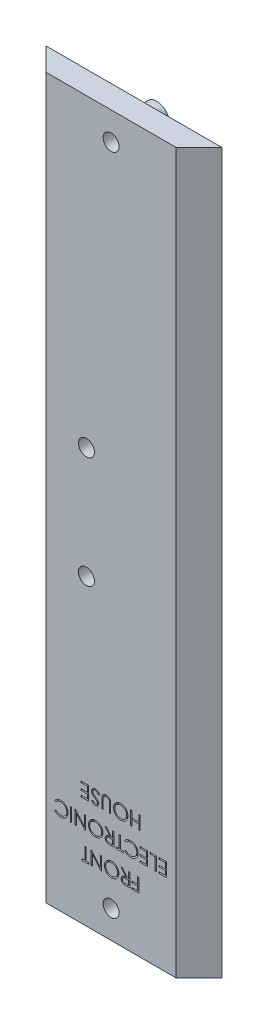
SolidWorks part; units mm, degrees
ref_plane "Front Plane" through (0, 0, 0) normal (1, 0, 0) x (0, 1, 0)
ref_plane "Top Plane" through (0, 0, 0) normal (0, 0, 1) x (0, 1, 0)
ref_plane "Right Plane" through (0, 0, 0) normal (0, 1, 0) x (-1, 0, 0)
sketch "Sketch3" plane through (0, 0, 0) normal (0, 0, 1) x (0, 1, 0)
  line L1 (0, 0) -> (157, 0)
  line L2 (0, 0) -> (0, 39.86)
  line L3 (0, 39.86) -> (157, 39.86)
  line L4 (157, 0) -> (157, 39.86)
extrude "Boss-Extrude1" add sketch "Sketch3" along normal blind 5
sketch "Sketch4" plane through (0, 0, 0) normal (0, -1, 0) x (1, 0, 0)
  line L0 (-39.86, 5) -> (-34.8616, 5)
  line L5 (-39.86, 5) -> (0, 5) construction
  line L6 (-34.8616, 5) -> (-39.86, 0)
  line L7 (-39.86, 0) -> (-39.86, 5)
  line L8 (0, 0) -> (0, 5)
  line L9 (0, 5) -> (-5, 5)
  line L10 (-5, 5) -> (0, 0)
extrude "Cut-Extrude2" cut sketch "Sketch4" against normal blind 157
sketch "Sketch6" plane through (0, 0, 5) normal (0, 0, 1) x (1, 0, 0)
  line L0 (-34.8616, 157) -> (-5, 0) construction
  line L1 (-5, 157) -> (-34.8616, 0) construction
  line L3 (-34.8616, 78.5) -> (-25.3316, 78.5) construction
  line L4 (-34.8616, 157) -> (-34.8616, 0) construction
  line L5 (-25.3316, 90.7) -> (-25.3316, 66.3) construction
  circle A0 centre (-19.9308, 6.08) radius 1.75
  circle A5 centre (-19.9308, 151.28) radius 1.75
  circle A6 centre (-25.3316, 90.7) radius 1.75
  circle A7 centre (-25.3316, 66.3) radius 1.75
  point P19 (-19.9308, 78.5)
  point P26 (-25.3316, 78.5)
extrude "Cut-Extrude3" cut sketch "Sketch6" against normal blind 5
sketch "Sketch7" plane through (0, 0, 0) normal (0, 0, -1) x (1, 0, 0)
  line L0 (-33.801, -65.3122) -> (-16.8606, -67.2423) construction
  line L1 (-16.8606, -67.2423) -> (-16.9738, -68.2359) construction
  line L2 (-33.801, -65.3122) -> (-36.9673, -93.1024) construction
  line L3 (-36.9673, -93.1024) -> (-33.7807, -93.523) construction
  line L4 (-33.7807, -93.523) -> (-33.801, -65.3122) construction
  line L5 (-16.9738, -68.2359) -> (-16.9738, -67.5359) construction
  circle A0 centre (-26.33, -20) radius 2.75
  circle A1 centre (-13.53, -20) radius 2.75
  circle A2 centre (-13.53, -40.35) radius 2.75
  circle A3 centre (-26.33, -40.35) radius 2.75
  circle A8 centre (-19.9308, -6.08) radius 2.75
  circle A10 centre (-19.9308, -151.28) radius 2.75
  circle A13 centre (-33.7807, -93.523) radius 2.75
  circle A14 centre (-33.801, -65.3122) radius 2.75
  circle A15 centre (-16.9738, -68.2359) radius 2.75 construction
  circle A16 centre (-16.9738, -67.5359) radius 2.75
  point P18 (-19.9308, -66.3)
sketch "Sketch8" plane through (0, 0, 0) normal (0, 0, -1) x (1, 0, 0)
  line L0 (-25.3316, -66.3) -> (-25.3316, -65.31) construction
  line L1 (-25.3316, -65.31) -> (-33.8016, -65.31) construction
  line L2 (-25.3316, -66.3) -> (-16.9716, -66.3) construction
  line L3 (-16.9716, -66.3) -> (-16.9716, -67.54) construction
  line L4 (-25.3316, -90.7) -> (-33.7816, -90.7) construction
  line L5 (-33.7816, -90.7) -> (-33.7816, -93.52) construction
  circle A0 centre (-26.33, -20) radius 1.7124
  circle A3 centre (-26.33, -40.35) radius 1.7124
  circle A7 centre (-13.53, -40.35) radius 1.7124
  circle A8 centre (-13.53, -20) radius 1.7124
  circle A10 centre (-19.9308, -6.08) radius 1.7124
  circle A12 centre (-19.9308, -151.28) radius 1.75
  circle A13 centre (-33.8016, -65.31) radius 1.75
  circle A14 centre (-16.9716, -67.54) radius 1.75
  circle A15 centre (-33.7816, -93.52) radius 1.75
extrude "Boss-Extrude3" add sketch "Sketch7" along normal blind 5
extrude "Cut-Extrude5" cut sketch "Sketch8" along normal blind 5
sketch "Sketch12" plane through (0, 157, 0) normal (0, 1, 0) x (-1, 0, 0)
  line L0 (0, 0) -> (0.3946, -0.307)
  line L1 (0.3946, -0.307) -> (5.7017, 5)
  line L2 (5, 5) -> (34.8616, 5) construction
  line L3 (5.7017, 5) -> (5, 5)
  line L4 (5, 5) -> (0, 0)
  line L5 (39.86, 0) -> (39.5064, -0.3536)
  line L6 (39.5064, -0.3536) -> (34.1529, 5)
  line L7 (34.1529, 5) -> (34.8616, 5)
  line L8 (34.8616, 5) -> (39.86, 0)
extrude "Cut-Extrude8" cut sketch "Sketch12" against normal blind 157
sketch "Sketch13" plane through (0, 157, 0) normal (0, 1, 0) x (-1, 0, 0)
  line L0 (0.7017, 0) -> (5.7017, 5)
  line L1 (5.7017, 5) -> (34.1529, 5)
  line L2 (34.1529, 5) -> (39.1529, 0)
  line L3 (0.7017, 0) -> (39.1529, 0)
extrude "Boss-Extrude5" add sketch "Sketch13" along normal blind 0.4
sketch "Sketch14" plane through (0, 0, 5) normal (0, 0, 1) x (1, 0, 0)
  line L0 (-19.9273, 0) -> (-19.9273, 15) construction
  line L1 (-34.1529, 0) -> (-5.7017, 0) construction
  line L2 (-7.4273, 15) -> (-32.4273, 15) construction
  text T0 "FRONT\r\nELECTRONICS\r\nHOUSE\r\n" font "Century Gothic" height 3
  point P7 (-19.9273, 15)
extrude "Cut-Extrude9" cut sketch "Sketch14" against normal blind 1
